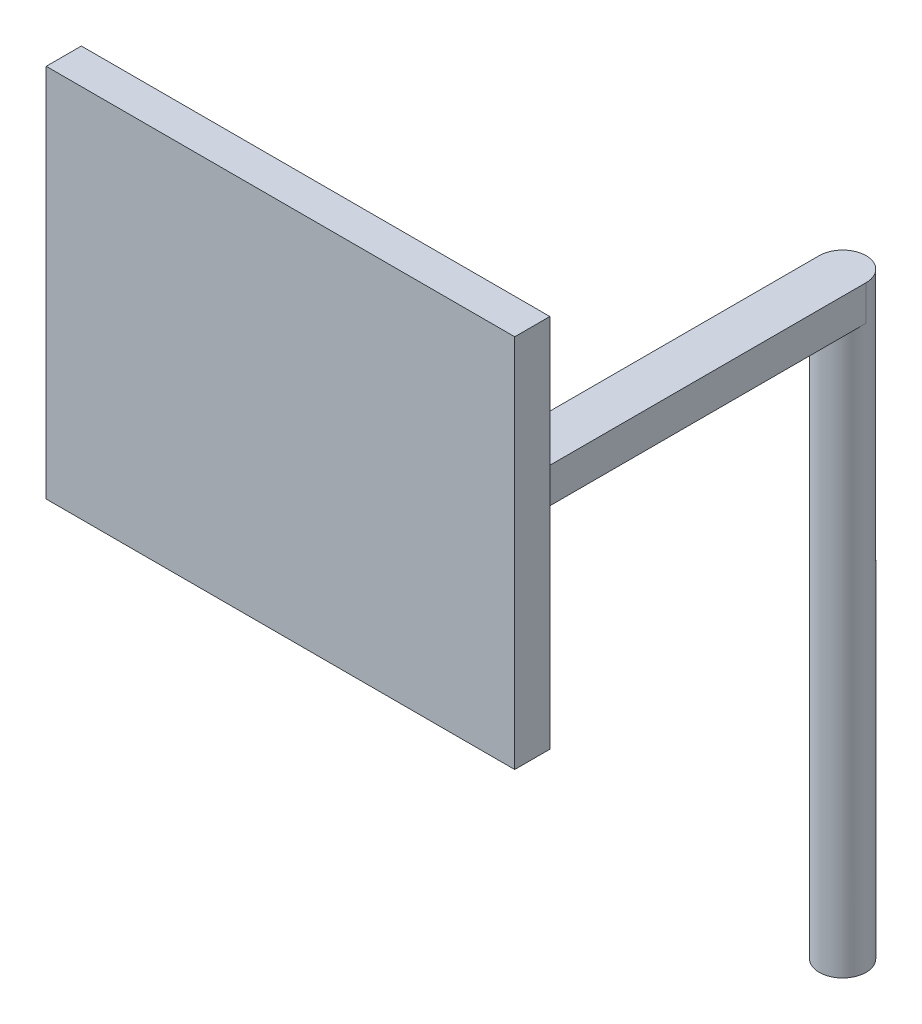
SolidWorks part; units mm, degrees
material "Balsa"
ref_plane "Front Plane" through (0, 0, 0) normal (0, 0, 1) x (1, 0, 0)
ref_plane "Top Plane" through (0, 0, 0) normal (0, 1, 0) x (1, 0, 0)
ref_plane "Right Plane" through (0, 0, 0) normal (1, 0, 0) x (0, 0, -1)
sketch "Sketch1" plane through (0, 0, 0) normal (0, 1, 0) x (1, 0, 0)
  circle A0 centre (0, 0) radius 5
  dimension "D1" = 10
extrude "branch" add sketch "Sketch1" along normal blind 120
sketch "Sketch2" plane through (0, 120, 0) normal (0, 1, 0) x (1, 0, 0)
  line L0 (-5, 0) -> (-5, -120)
  line L1 (5, 0) -> (5, -120)
  line L2 (-5, -120) -> (5, -120)
  circle A0 centre (0, 0) radius 5 construction
  circle A2 centre (0, 0) radius 5
  arc A3 (5, 0) -> (-5, 0) centre (0, 0) ccw
  dimension "D2" = 120
  dimension "D1" = 0
extrude "Boss-Extrude1" add sketch "Sketch2" along normal blind 7.5
sketch "Sketch3" plane through (0, 0, 120) normal (0, 0, 1) x (1, 0, 0)
  line L1 (-50, 200) -> (50, 200)
  line L2 (0, 200) -> (0, 120) construction
  line L12 (50, 120) -> (-50, 120)
  line L13 (-5, 120) -> (5, 120) construction
  line L14 (-50, 120) -> (-50, 200)
  line L15 (50, 120) -> (50, 200)
  dimension "D1" = 50
  dimension "D2" = 80
extrude "Boss-Extrude2" add sketch "Sketch3" against normal blind 7.5
